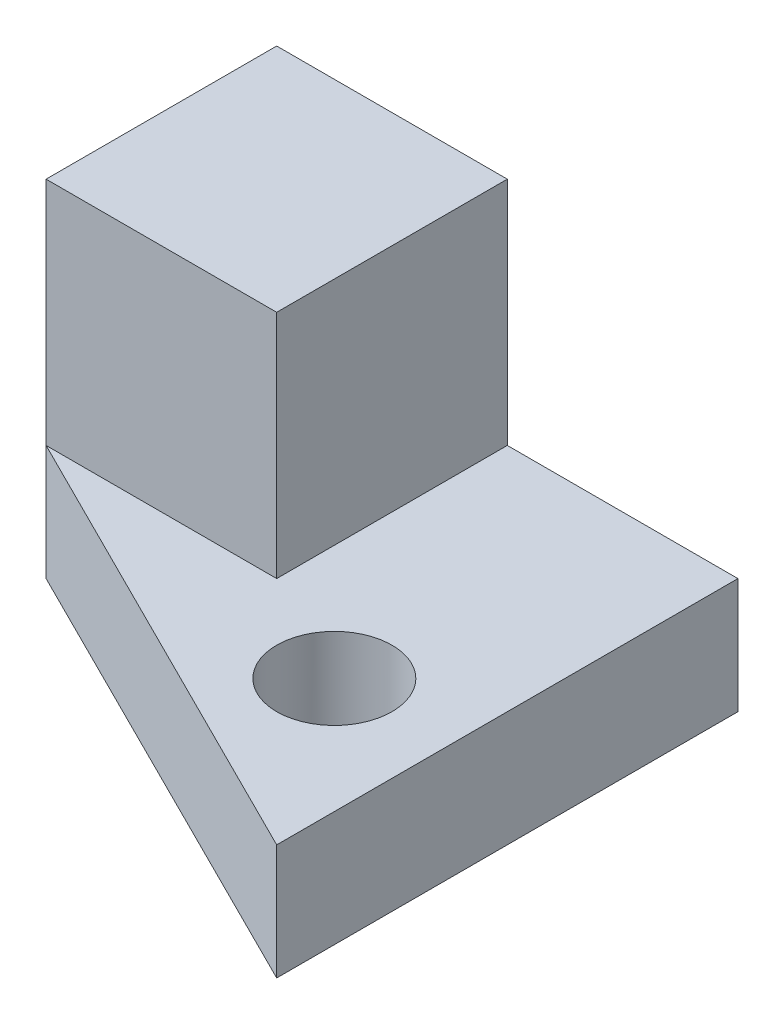
SolidWorks part; units mm, degrees
ref_plane "Front Plane" through (0, 0, 0) normal (0, 0, 1) x (1, 0, 0)
ref_plane "Top Plane" through (0, 0, 0) normal (0, 1, 0) x (1, 0, 0)
ref_plane "Right Plane" through (0, 0, 0) normal (1, 0, 0) x (0, 0, -1)
sketch "Sketch1" plane through (0, 0, 0) normal (0, 1, 0) x (1, 0, 0)
  line L0 (0, 0) -> (0, 1016)
  line L1 (0, 0) -> (1016, 0)
  line L2 (0, 1016) -> (1016, 1016)
  line L3 (1016, 1016) -> (1016, 0)
  point P4 (1016, 0)
  dimension "D1" = 1016
  dimension "D2" = 1016
  dimension "D3" = 1016
  dimension "D4" = 1016
extrude "Boss-Extrude1" add sketch "Sketch1" along normal blind 1016 contours L0 L2 L3 L1
sketch "Sketch2" plane through (0, 1016, 0) normal (0, 1, 0) x (1, 0, 0)
  line L0 (0, 0) -> (1016, 0)
  line L1 (1016, 0) -> (0, 508)
  line L2 (0, 0) -> (0, 1016) construction
  line L3 (0, 508) -> (0, 0)
  point P7 (0, 511.0614)
  dimension "D1" = 508
extrude "Cut-Extrude1" cut sketch "Sketch2" against normal blind 1016
sketch "Sketch3" plane through (0, 1016, 0) normal (0, 1, 0) x (1, 0, 0)
  line L0 (0, 508) -> (508, 508)
  line L1 (508, 508) -> (508, 1016)
  line L2 (0, 1016) -> (1016, 1016) construction
  line L3 (508, 1016) -> (1016, 1016)
  line L4 (1016, 1016) -> (1016, 0)
  line L5 (1016, 0) -> (0, 508)
  point P11 (1020.9488, 1016)
  dimension "D1" = 508
  dimension "D2" = 508
  dimension "D3" = 508
extrude "Cut-Extrude2" cut sketch "Sketch3" against normal blind 762
sketch "Sketch4" plane through (0, 0, -508) normal (0, 0, 1) x (1, 0, 0)
  line L0 (0, 1016) -> (0, 762)
  line L1 (0, 762) -> (508, 762)
  line L2 (508, 254) -> (508, 1016) construction
  line L3 (0, 254) -> (0, 1016) construction
  line L4 (508, 762) -> (508, 1016)
  line L5 (508, 1016) -> (0, 1016)
  dimension "D1" = 254
  dimension "D2" = 508
extrude "Cut-Extrude3" cut sketch "Sketch4" against normal blind 762
sketch "Sketch5" plane through (0, 254, 0) normal (0, 1, 0) x (1, 0, 0)
  circle A0 centre (762, 381) radius 127
extrude "Cut-Extrude4" cut sketch "Sketch5" against normal blind 762
